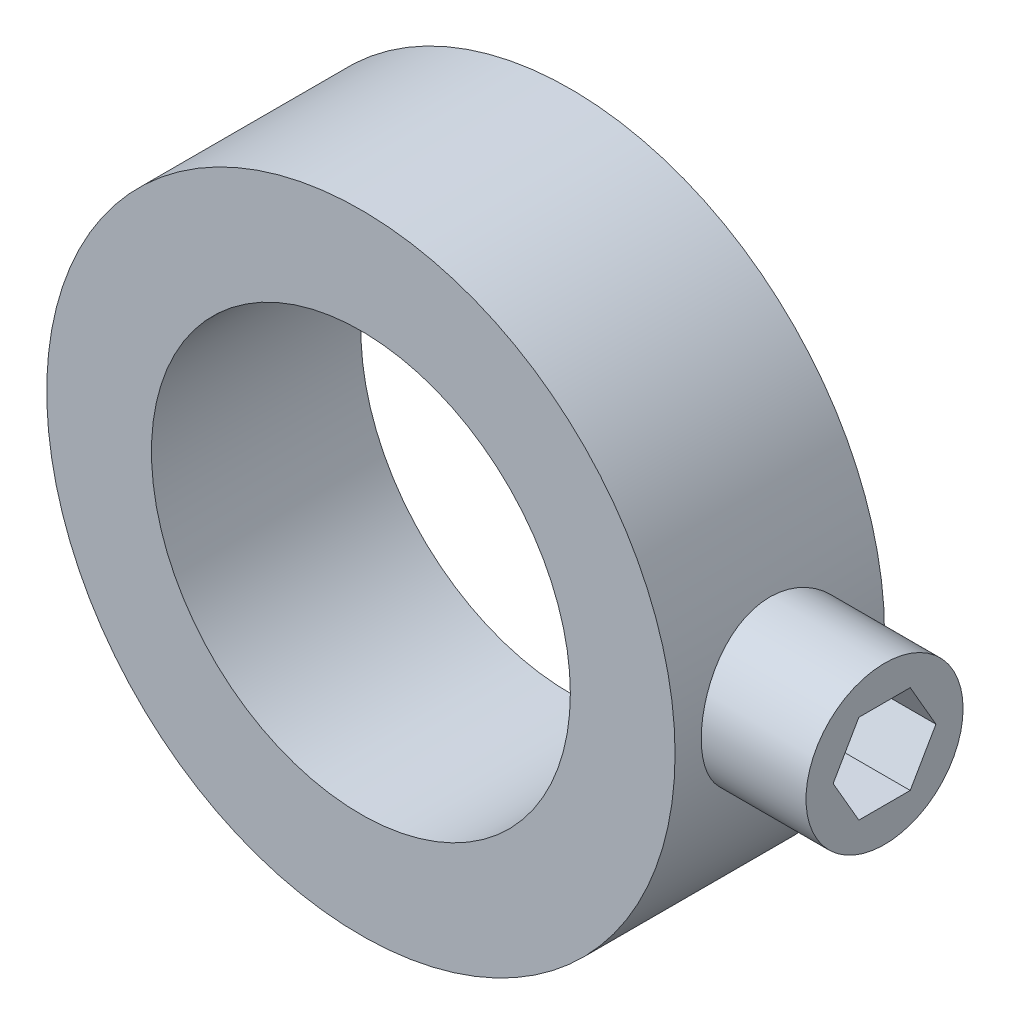
SolidWorks part; units mm, degrees
material "1060 Alloy"
ref_plane "Front Plane" through (0, 0, 0) normal (0, 0, 1) x (1, 0, 0)
ref_plane "Top Plane" through (0, 0, 0) normal (0, 1, 0) x (1, 0, 0)
ref_plane "Right Plane" through (0, 0, 0) normal (1, 0, 0) x (0, 0, -1)
sketch "Sketch1" plane through (0, 0, 0) normal (0, 0, 1) x (1, 0, 0)
  circle A0 centre (0, 0) radius 4
  circle A1 centre (0, 0) radius 6
  dimension "D1" = 8
  dimension "D2" = 12
extrude "Boss-Extrude1" add sketch "Sketch1" along normal blind 4
ref_plane "Plane1" through (6, 0, 0) normal (1, 0, 0) x (0, 0, -1)
sketch "Sketch2" plane through (6, 0, 0) normal (1, 0, 0) x (0, 0, -1)
  circle A0 centre (-2, 0) radius 1.5
  dimension "D1" = 3
extrude "Boss-Extrude2" add sketch "Sketch2" along normal blind 2 and the other way blind 1
sketch "Sketch3" plane through (8, 0, 0) normal (1, 0, 0) x (0, 0, -1)
  line L0 (-2.4907, 0.85) -> (-1.5093, 0.85)
  line L1 (-2.4907, -0.85) -> (-1.5093, -0.85)
  line L2 (-1.5093, -0.85) -> (-1.0185, 0)
  line L3 (-1.0185, 0) -> (-1.5093, 0.85)
  line L4 (-2.4907, 0.85) -> (-2.9815, 0)
  line L5 (-2.9815, 0) -> (-2.4907, -0.85)
  line L6 (-2.4907, 0.85) -> (-2, 0) construction
  line L7 (-2, 0) -> (-1.5093, -0.85) construction
  line L8 (-2.4907, -0.85) -> (-2, 0) construction
  line L9 (-2, 0) -> (-1.5093, 0.85) construction
  line L10 (-1.0185, 0) -> (-2, 0) construction
  line L11 (-2, 0) -> (-2.9815, 0) construction
  circle A0 centre (-2, 0) radius 1.5 construction
  dimension "D1" = 0
  dimension "D2" = 60
  dimension "D3" = 60
  dimension "D4" = 1.7
extrude "Cut-Extrude1" cut sketch "Sketch3" against normal blind 1.5
